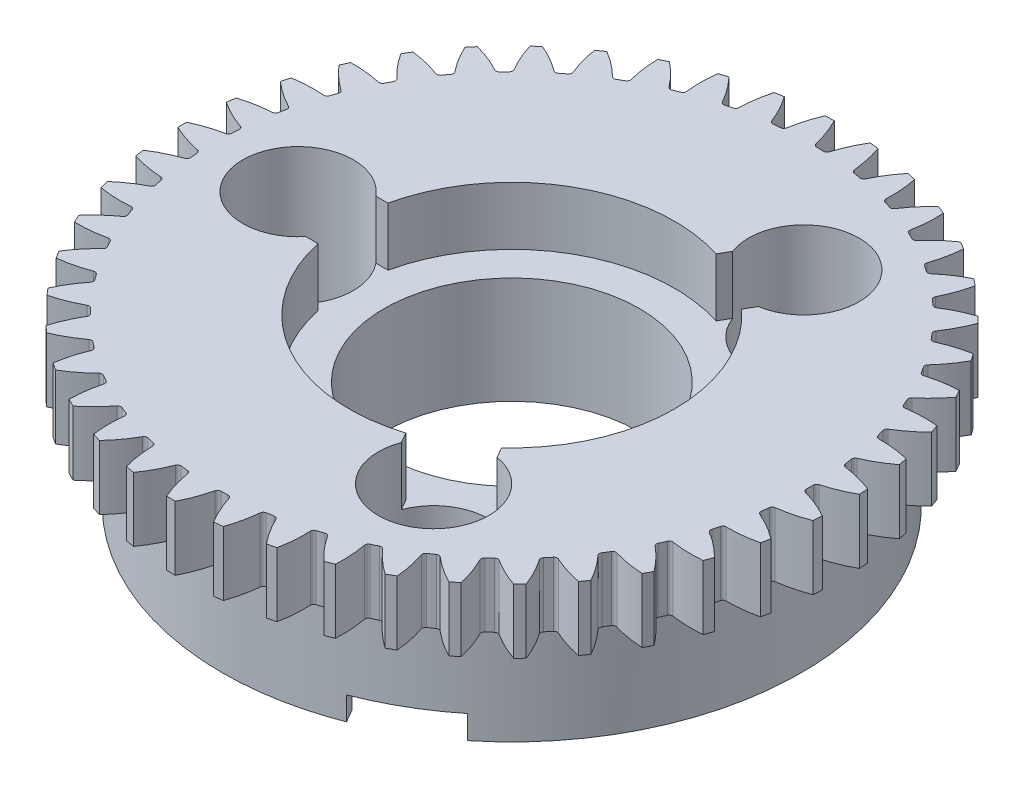
SolidWorks part; units mm, degrees
ref_plane "Front Plane" through (0, 0, 0) normal (0, 0, 1) x (1, 0, 0)
ref_plane "Top Plane" through (0, 0, 0) normal (0, 1, 0) x (1, 0, 0)
ref_plane "Right Plane" through (0, 0, 0) normal (1, 0, 0) x (0, 0, -1)
sketch "Sketch2" plane through (0, 0, 0) normal (0, 1, 0) x (1, 0, 0)
  circle A0 centre (0, 0) radius 26.56
  circle A1 centre (-19.0525, 0) radius 4.926
  circle A2 centre (9.5262, 16.4999) radius 4.926
  circle A3 centre (9.5262, -16.4999) radius 4.926
  circle A5 centre (0, 0) radius 11.375
  point P2 (0, 0)
  point P11 (0, 0)
  point P12 (13.6656, 4.178)
  dimension "D2" = 3
  dimension "D1" = 22.75
  dimension "D4" = 53.12
  dimension "D5" = 9.852
  dimension "D3" = 19.0525
extrude "Boss-Extrude2" add sketch "Sketch2" along normal blind 5.72
sketch "Sketch4" plane through (0, 0, 0) normal (0, -1, 0) x (1, 0, 0)
  circle A0 centre (9.5262, 16.4999) radius 4.926 construction
  circle A1 centre (9.5262, 16.4999) radius 4.926
  circle A2 centre (0, 0) radius 9.625
  circle A19 centre (0, 0) radius 25.815
  point P6 (-1.3086, -0.0126)
  point P13 (12.187, -21.1085)
  point P15 (-24.374, 0)
  point P17 (12.187, 21.1085)
  point P18 (-12.5475, 0)
  point P25 (16.9495, -21.1085)
  point P26 (16.9495, 21.1085)
  point P27 (-26.7552, 4.1244)
  point P28 (9.8057, 25.2329)
  point P29 (9.8057, -25.2329)
  point P30 (-26.7552, -4.1244)
  point P31 (16.4175, -16.723)
  point P36 (16.4175, 16.723)
  point P46 (13.9118, 4.2533)
  circle M1 centre (9.5262, -16.4999) radius 4.926
  circle M2 centre (-19.0525, 0) radius 4.926
  circle M4 centre (0, 0) radius 11.375
  circle M5 centre (9.5262, 16.4999) radius 4.926
  dimension "D1" = 19.25
extrude "Boss-Extrude3" add sketch "Sketch4" along normal blind 8.98 contours A19 M1 M5 M4 M2
sketch "Sketch7" plane through (0, 5.72, 0) normal (0, 1, 0) x (1, 0, 0)
  line L0 (0, 0) -> (9.5262, 16.4999) construction
  line L1 (9.7843, -10.7013) -> (10.3258, -11.6393)
  line L2 (9.7843, 10.7013) -> (10.3258, 11.6393)
  line L4 (4.3755, -13.8241) -> (4.917, -14.762)
  line L5 (-14.1597, -3.1228) -> (-15.2428, -3.1228)
  line L6 (-14.1597, 3.1228) -> (-15.2428, 3.1228)
  line L7 (4.3755, 13.8241) -> (4.917, 14.762)
  arc A0 (4.3755, 13.8241) -> (-14.1597, 3.1228) centre (0, 0) ccw
  arc A1 (10.3258, -11.6393) -> (4.917, -14.762) centre (9.5262, -16.4999) ccw
  arc A2 (-15.2428, -3.1228) -> (-15.2428, 3.1228) centre (-19.0525, 0) ccw
  circle A4 centre (9.5262, 16.4999) radius 4.926 construction
  arc A5 (4.917, 14.762) -> (10.3258, 11.6393) centre (9.5262, 16.4999) ccw
  arc A6 (-14.1597, -3.1228) -> (4.3755, -13.8241) centre (0, 0) ccw
  arc A8 (9.7843, -10.7013) -> (9.7843, 10.7013) centre (0, 0) ccw
  point P21 (0, 0)
  point P28 (0, 0)
  point P29 (0, 0)
  dimension "D1" = 29
  dimension "D2" = 3
extrude "Cut-Extrude7" cut sketch "Sketch7" against normal blind 5.178
sketch "Sketch10" plane through (0, 5.72, 0) normal (0, 1, 0) x (1, 0, 0)
  circle A3 centre (0, 0) radius 25.56
  circle A4 centre (0, 0) radius 25.56
  dimension "D1" = 1
sketch "Sketch12" plane through (0, 5.72, 0) normal (0, 1, 0) x (1, 0, 0)
  line L0 (0, 0) -> (15.065, -26.0933) construction
  line L1 (13.28, -23.0016) -> (14.4058, -22.3516) construction
  arc A0 (11.9245, -23.7327) -> (14.5908, -22.1933) centre (0, 0) ccw
  circle A1 centre (0, 0) radius 26.56 construction
  circle A2 centre (0, 0) radius 29.38
  arc A3 (14.5908, -22.1933) -> (14.4715, -22.5401) centre (14.7557, -22.4439) ccw
  circle A4 centre (0, 0) radius 26.56 construction
  arc A5 (15.029, -25.2451) -> (14.4715, -22.5401) centre (3.8151, -26.1463) ccw
  arc A6 (14.3484, -25.638) -> (12.2846, -23.8027) centre (20.7358, -16.3771) cw
  arc A7 (11.9245, -23.7327) -> (12.2846, -23.8027) centre (12.0592, -24.0007) cw
  point P18 (25.3995, 7.7654)
  circle M13 centre (0, 0) radius 26.56
  dimension "D1" = 0.3
  dimension "D2" = 58.76
  dimension "D3" = 30.13
  dimension "D4" = 1.3
  dimension "D5" = 11.25
extrude "Boss-Extrude4" add sketch "Sketch12" against normal up to surface (5.72 mm away) contours A7 A6 A2 A5 A3 M13
pattern_circular "CirPattern2" count 45 over 360 about axis through (0, 0, 0) along (0, 1, 0) of "Boss-Extrude4"
sketch "Sketch9" plane through (0, -8.98, 0) normal (0, -1, 0) x (1, 0, 0)
  line L0 (9.5262, -16.4999) -> (0, 0) construction
  line L1 (8.6529, -22.8905) -> (9.3331, -24.0688)
  line L2 (15.4974, -18.9389) -> (16.1776, -20.1171)
  line L3 (-24.1502, 3.9517) -> (-25.5108, 3.9517)
  line L4 (-24.1502, -3.9517) -> (-25.5108, -3.9517)
  line L5 (15.4974, 18.9389) -> (16.1776, 20.1171)
  line L6 (8.6529, 22.8905) -> (9.3331, 24.0688)
  arc A2 (-24.1502, -3.9517) -> (-24.1502, 3.9517) centre (-19.0525, 0) ccw
  arc A3 (15.9762, -16.4999) -> (15.9762, -16.4999) centre (9.5262, -16.4999) ccw
  arc A4 (15.4974, -18.9389) -> (8.6529, -22.8905) centre (9.5262, -16.4999) ccw
  arc A5 (-25.5108, 3.9517) -> (-25.5108, -3.9517) centre (0, 0) ccw
  circle A6 centre (0, 0) radius 25.815 construction
  arc A7 (9.3331, -24.0688) -> (16.1776, -20.1171) centre (0, 0) ccw
  arc A8 (8.6529, 22.8905) -> (15.4974, 18.9389) centre (9.5263, 16.4999) ccw
  arc A9 (16.1776, 20.1171) -> (9.3331, 24.0688) centre (0, 0) ccw
  point P9 (0, 0)
  point P22 (0, 0)
  dimension "D1" = 1.524
  dimension "D2" = 3
extrude "Cut-Extrude8" cut sketch "Sketch9" against normal blind 2.0875
